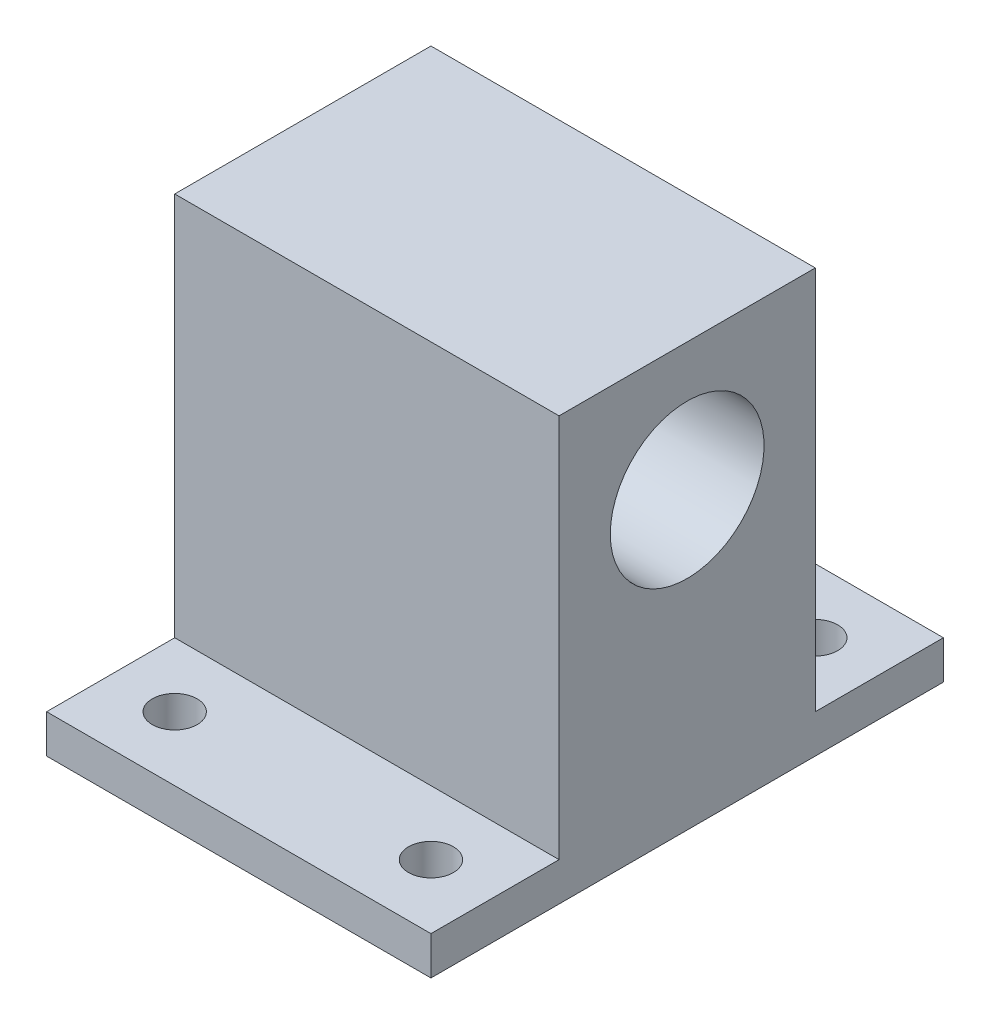
SolidWorks part; units mm, degrees
ref_plane "Front Plane" through (0, 0, 0) normal (0, 0, 1) x (1, 0, 0)
ref_plane "Top Plane" through (0, 0, 0) normal (0, 1, 0) x (1, 0, 0)
ref_plane "Right Plane" through (0, 0, 0) normal (1, 0, 0) x (0, 0, -1)
sketch "Sketch1" plane through (0, 0, 0) normal (0, 1, 0) x (1, 0, 0)
  line L1 (-15, 20) -> (15, 20)
  line L2 (-15, 20) -> (-15, -20)
  line L3 (-15, -20) -> (15, -20)
  line L4 (15, 20) -> (15, -20)
  line L5 (-15, 20) -> (15, -20) construction
  line L6 (-15, -20) -> (15, 20) construction
  circle A0 centre (-10, 15) radius 1.75
  circle A1 centre (10, 15) radius 1.75
  circle A2 centre (10, -15) radius 1.75
  circle A3 centre (-10, -15) radius 1.75
  point P0 (0, 0)
  point P10 (10.4889, -13.9853)
  dimension "D3" = 3.5
  dimension "D1" = 30
  dimension "D2" = 40
  dimension "D4" = 5
  dimension "D5" = 5
  dimension "D8" = 20
  dimension "D9" = 36.0555
  dimension "D10" = 30
  dimension "D6" = 2
  dimension "D7" = 2
extrude "Boss-Extrude2" add sketch "Sketch1" along normal blind 3
sketch "Sketch2" plane through (0, 3, 0) normal (0, 1, 0) x (1, 0, 0)
  line L0 (15, -20) -> (15, 20) construction
  line L1 (-15, 10) -> (15, 10)
  line L2 (-15, 10) -> (-15, -10)
  line L3 (-15, -10) -> (15, -10)
  line L4 (15, 10) -> (15, -10)
  line L5 (-15, 10) -> (15, -10) construction
  line L6 (-15, -10) -> (15, 10) construction
  point P0 (0, 0)
  dimension "D1" = 20
extrude "Boss-Extrude3" add sketch "Sketch2" along normal blind 30
sketch "Sketch3" plane through (-15, 0, 0) normal (-1, 0, 0) x (0, 0, 1)
  line L0 (0, -1.65) -> (0, 1.65) construction
  line L1 (-10, 33) -> (10, 33) construction
  circle A0 centre (0, 23) radius 6
  dimension "D1" = 12
  dimension "D2" = 10
extrude "Cut-Extrude1" cut sketch "Sketch3" against normal blind 30
